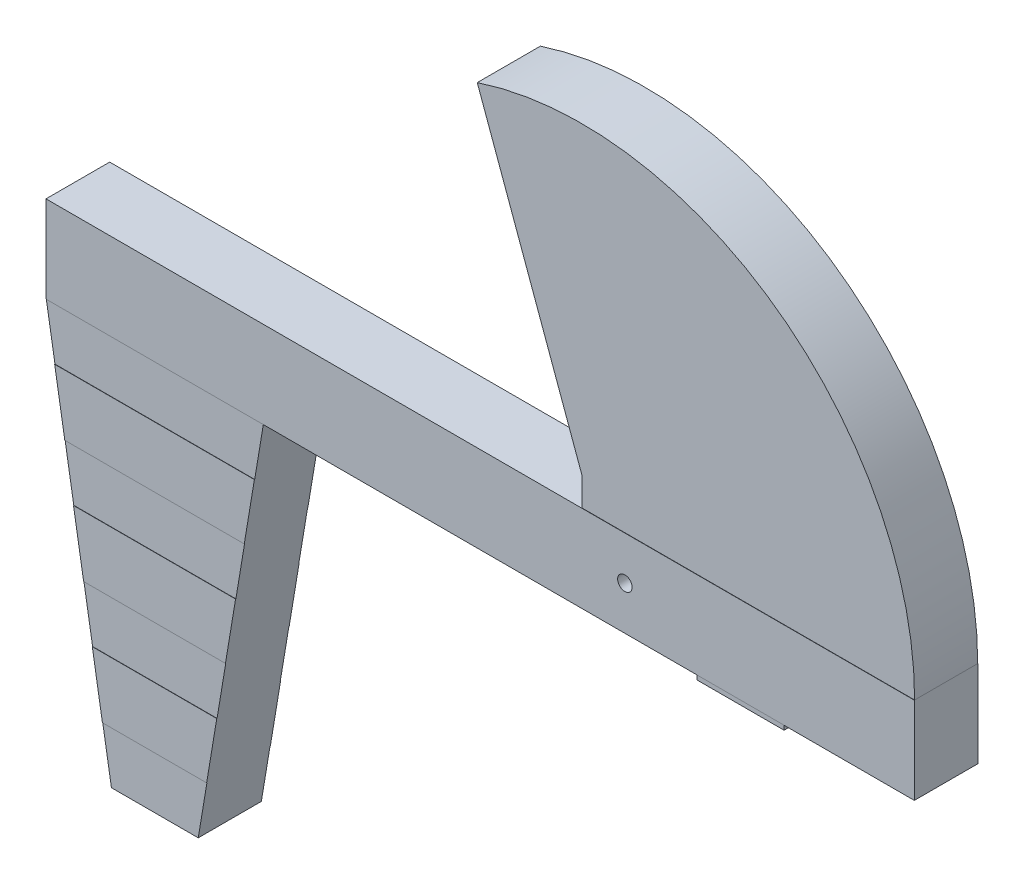
SolidWorks part; units mm, degrees
material "Pin"
ref_plane "Plan de face" through (0, 0, 0) normal (0, 0, 1) x (1, 0, 0)
ref_plane "Plan de dessus" through (0, 0, 0) normal (0, 1, 0) x (1, 0, 0)
ref_plane "Plan de droite" through (0, 0, 0) normal (1, 0, 0) x (0, 0, -1)
sketch "Esquisse1" plane through (0, 0, 0) normal (0, 0, 1) x (1, 0, 0)
  line L0 (-125, -15) -> (100, -15)
  line L1 (100, -15) -> (100, 15)
  line L2 (-51.101, 124.1866) -> (-15, 25)
  line L3 (-15, 25) -> (-15, 15)
  line L4 (-15, 15) -> (-200, 15)
  line L5 (-200, 15) -> (-200, -15)
  line L6 (-200, -15) -> (-177.5, -150)
  line L7 (-177.5, -150) -> (-147.5, -150)
  line L8 (-147.5, -150) -> (-125, -15)
  circle A0 centre (0, 0) radius 2.5
  arc A1 (100, 15) -> (-51.101, 124.1866) centre (-15, 15) ccw
  dimension "D1" = 15
  dimension "D2" = 100
  dimension "D7" = 115
  dimension "D9" = 5
  dimension "D3" = 30
  dimension "D4" = 225
  dimension "D5" = 185
  dimension "D6" = 10
  dimension "D8" = 70
  dimension "D10" = 135
  dimension "D11" = 30
  dimension "D12" = 22.5
  dimension "D13" = 22.5
extrude "Boss.-Extru.1" add sketch "Esquisse1" along normal mid plane 22
sketch "Esquisse2" plane through (0, 0, 11) normal (0, 0, 1) x (1, 0, 0)
  line L0 (-200, 15) -> (-200, -15) construction
  line L1 (100, 15) -> (-51.101, 15)
  line L2 (100, 15) -> (100, 166.101)
  line L3 (100, 166.101) -> (-51.101, 166.101)
  line L4 (-51.101, 15) -> (-51.101, 166.101)
  line L5 (-125, -15) -> (-200, -15)
  line L6 (-125, -15) -> (-125, -33)
  line L7 (-125, -33) -> (-200, -33)
  line L8 (-200, -15) -> (-200, -33)
  line L9 (-177.5, -150) -> (-147.5, -150) construction
  line L10 (-200, -54) -> (-125, -54)
  line L11 (-200, -54) -> (-200, -72)
  line L12 (-200, -72) -> (-125, -72)
  line L13 (-125, -54) -> (-125, -72)
  line L14 (-200, -93) -> (-125, -93)
  line L15 (-200, -93) -> (-200, -111)
  line L16 (-200, -111) -> (-125, -111)
  line L17 (-125, -93) -> (-125, -111)
  line L18 (-200, -132) -> (-125, -132)
  line L19 (-200, -132) -> (-200, -150)
  line L20 (-200, -150) -> (-125, -150)
  line L21 (-125, -132) -> (-125, -150)
  line L22 (-200, -33) -> (-200, -54) construction
  line L23 (-200, -93) -> (-200, -72) construction
  line L24 (-200, -111) -> (-200, -132) construction
  dimension "D1" = 18
  dimension "D2" = 21
extrude "Enlèv. mat.-Extru.1" cut sketch "Esquisse2" against normal blind 0.1
mirror "Symétrie1" about plane through (0, 0, 0) normal (0, 0, 1)
sketch "Esquisse3" plane through (0, -15, 0) normal (0, -1, 0) x (1, 0, 0)
  line L0 (-200, 11) -> (100, 11) construction
  line L1 (25, 11) -> (55, 11)
  line L2 (25, 11) -> (25, -11)
  line L3 (25, -11) -> (55, -11)
  line L4 (55, 11) -> (55, -11)
  line L5 (-200, -11) -> (100, -11) construction
  line L6 (100, 11) -> (100, -11) construction
  dimension "D1" = 30
  dimension "D2" = 45
extrude "Boss.-Extru.2" add sketch "Esquisse3" along normal blind 1.5 separate body
